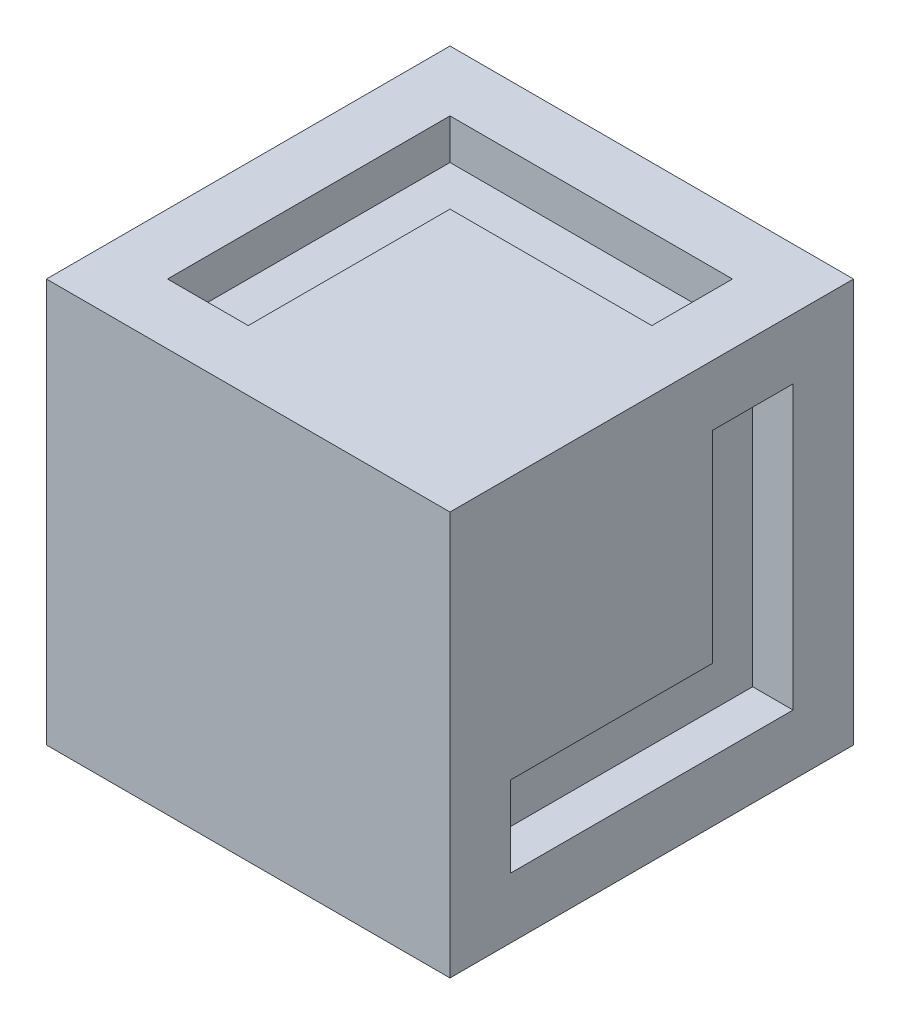
SolidWorks part; units mm, degrees
ref_plane "Front Plane" through (0, 0, 0) normal (0, 0, 1) x (1, 0, 0)
ref_plane "Top Plane" through (0, 0, 0) normal (0, 1, 0) x (1, 0, 0)
ref_plane "Right Plane" through (0, 0, 0) normal (1, 0, 0) x (0, 0, -1)
ref_plane "Plane1" through (0, 0, 5) normal (0, 0, 1) x (1, 0, 0)
sketch "Sketch1" plane through (0, 0, 5) normal (0, 0, 1) x (1, 0, 0)
  line L1 (10, 15) -> (30, 15)
  line L2 (10, 15) -> (10, 35)
  line L3 (10, 35) -> (30, 35)
  line L4 (30, 15) -> (30, 35)
extrude "Boss-Extrude1" add sketch "Sketch1" along normal blind 20
sketch "Sketch2" plane through (30, 0, 0) normal (1, 0, 0) x (0, 0, -1)
  line L0 (-8, 18) -> (-8, 32)
  line L1 (-8, 32) -> (-12, 32)
  line L2 (-12, 32) -> (-12, 22)
  line L3 (-12, 22) -> (-22, 22)
  line L4 (-22, 22) -> (-22, 18)
  line L5 (-22, 18) -> (-8, 18)
extrude "Cut-Extrude1" cut sketch "Sketch2" against normal blind 2
sketch "Sketch3" plane through (10, 0, 0) normal (-1, 0, 0) x (0, 0, 1)
  line L0 (8, 18) -> (8, 32)
  line L1 (8, 32) -> (12, 32)
  line L2 (12, 32) -> (12, 22)
  line L3 (12, 22) -> (22, 22)
  line L4 (22, 22) -> (22, 18)
  line L5 (22, 18) -> (8, 18)
extrude "Cut-Extrude2" cut sketch "Sketch3" against normal blind 2
sketch "Sketch4" plane through (0, 35, 0) normal (0, 1, 0) x (1, 0, 0)
  line L0 (13, -8) -> (27, -8)
  line L1 (27, -8) -> (27, -12)
  line L2 (27, -12) -> (17, -12)
  line L3 (17, -12) -> (17, -22)
  line L4 (17, -22) -> (13, -22)
  line L5 (13, -22) -> (13, -8)
extrude "Cut-Extrude3" cut sketch "Sketch4" against normal blind 2
sketch "Sketch5" plane through (0, 15, 0) normal (0, -1, 0) x (1, 0, 0)
  line L0 (13, 8) -> (27, 8)
  line L1 (27, 8) -> (27, 12)
  line L2 (27, 12) -> (17, 12)
  line L3 (17, 12) -> (17, 22)
  line L4 (17, 22) -> (13, 22)
  line L5 (13, 22) -> (13, 8)
extrude "Cut-Extrude4" cut sketch "Sketch5" against normal blind 2
sketch "Sketch6" plane through (0, 0, 5) normal (0, 0, -1) x (-1, 0, 0)
  line L0 (-13, 18) -> (-27, 18)
  line L1 (-27, 18) -> (-27, 22)
  line L2 (-27, 22) -> (-17, 22)
  line L3 (-17, 22) -> (-17, 32)
  line L4 (-17, 32) -> (-13, 32)
  line L5 (-13, 32) -> (-13, 18)
extrude "Cut-Extrude5" cut sketch "Sketch6" against normal blind 2
